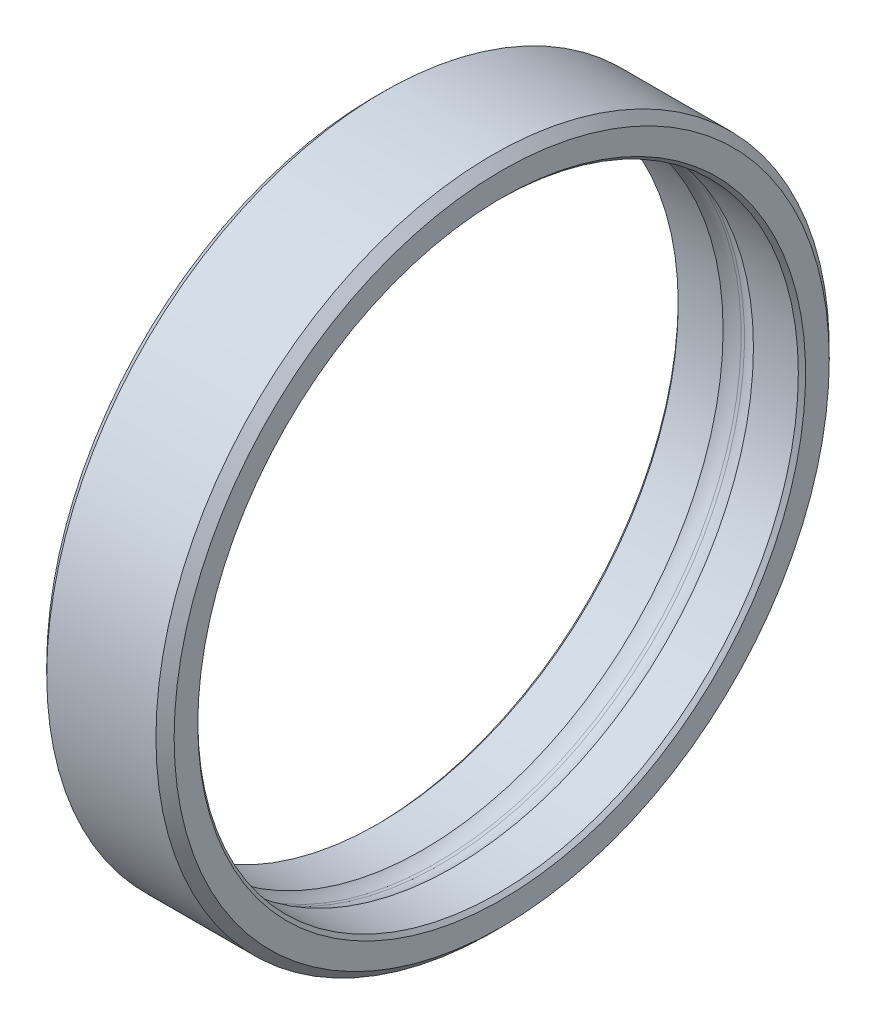
SolidWorks part; units mm, degrees
ref_plane "Спереди" through (0, 0, 0) normal (0, 0, 1) x (1, 0, 0)
ref_plane "Сверху" through (0, 0, 0) normal (0, 1, 0) x (1, 0, 0)
ref_plane "Справа" through (0, 0, 0) normal (1, 0, 0) x (0, 0, -1)
sketch "Эскиз1" plane through (0, 0, 0) normal (0, 0, 1) x (1, 0, 0)
  line L0 (0, 0) -> (41.2659, 0) construction
  line L1 (0, 0) -> (0, 30.251) construction
  line L2 (0.8334, 16.5) -> (3.5, 16.5)
  line L3 (-3.5, 16.5) -> (-0.8334, 16.5)
  line L4 (-3.5, 16.5) -> (-3.5, 18.5)
  line L5 (-3.5, 18.5) -> (3.5, 18.5)
  line L6 (3.5, 16.5) -> (3.5, 18.5)
  line L7 (0.0917, 16.75) -> (-0.0917, 16.75)
  arc A0 (-0.0917, 16.75) -> (-0.8334, 16.5) centre (0, 15.2528) ccw
  arc A1 (0.8334, 16.5) -> (0.0917, 16.75) centre (0, 15.2528) ccw
  point P14 (0, 16.75)
  dimension "D4" = 16.75
  dimension "D5" = 1.5
  dimension "D1" = 7
  dimension "D2" = 33
  dimension "D3" = 37
revolve "Повернуть1" add sketch "Эскиз1" angle 360 about L0
chamfer "Фаска1" distance 0.5 angle 45 2 edges at (3.5, 0, 18.5) (-3.5, 0, 18.5)
chamfer "Фаска2" distance 0.2 angle 45 2 edges at (-3.5, 0, 16.5) (3.5, 0, 16.5)
